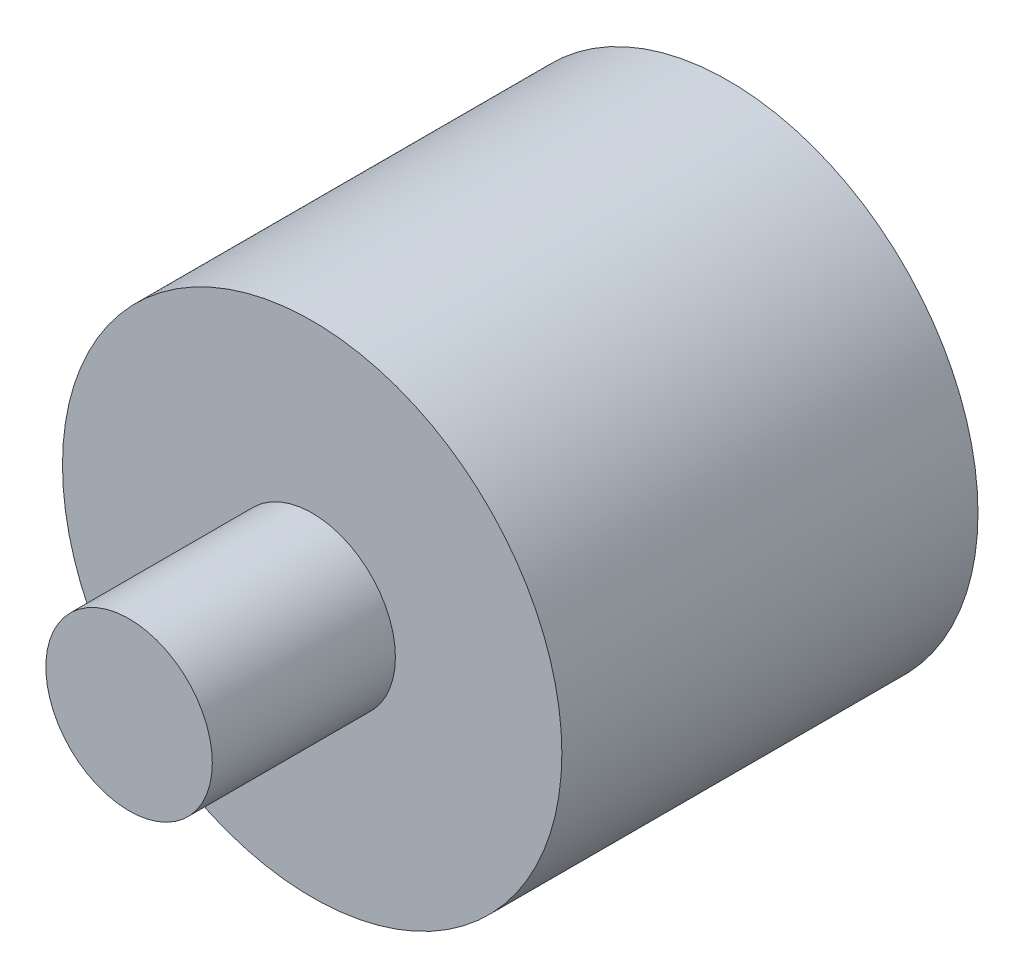
SolidWorks part; units mm, degrees
ref_plane "Plan1" through (0, 0, 0) normal (0, 0, 1) x (1, 0, 0)
ref_plane "Plan2" through (0, 0, 0) normal (0, 1, 0) x (1, 0, 0)
ref_plane "Plan3" through (0, 0, 0) normal (1, 0, 0) x (0, 0, -1)
sketch "Esquisse1" plane through (0, 0, 0) normal (0, 0, 1) x (1, 0, 0)
  circle A0 centre (0, 0) radius 10
  dimension "D1" = 20
extrude "Base-Extrusion" add sketch "Esquisse1" along normal blind 22
sketch "Esquisse2" plane through (0, 0, 22) normal (0, 0, 1) x (1, 0, 0)
  line L0 (0, 10) -> (0, 0)
  circle A0 centre (0, 0) radius 10
sketch "Esquisse3" plane through (0, 0, 0) normal (0, 0, -1) x (-1, 0, 0)
  circle A0 centre (0, 0) radius 30
extrude "Boss.-Extru.1" add sketch "Esquisse3" along normal blind 50
